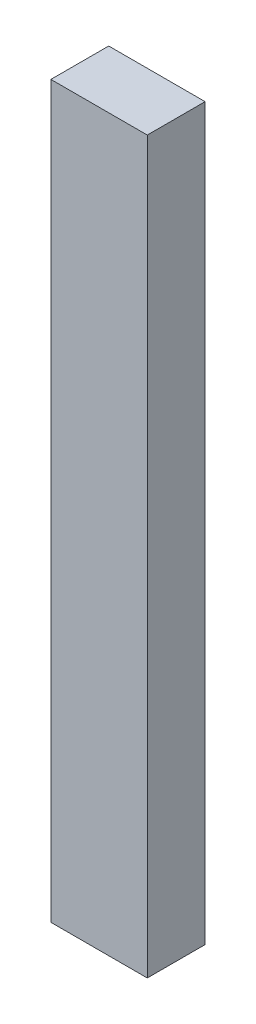
SolidWorks part; units mm, degrees
ref_plane "Front" through (0, 0, 0) normal (0, 0, 1) x (1, 0, 0)
ref_plane "Top" through (0, 0, 0) normal (0, 1, 0) x (1, 0, 0)
ref_plane "Right" through (0, 0, 0) normal (1, 0, 0) x (0, 0, -1)
sketch "Sketch1" plane through (0, 0, 0) normal (0, 0, 1) x (1, 0, 0)
  line L3 (63.5, 480.95) -> (63.5, 0) construction
  line L4 (0, 0) -> (480.95, 0)
  line L5 (480.95, 0) -> (480.95, 480.95)
  line L6 (480.95, 480.95) -> (0, 480.95)
  line L7 (0, 480.95) -> (0, 0)
  line L8 (0, 0) -> (63.5, 0)
  line L11 (0, 480.95) -> (0, 0)
  line L15 (63.5, 480.95) -> (63.5, 0)
  line L16 (63.5, 480.95) -> (0, 480.95)
  dimension "D1" = 0
extrude "Boss-Extrude1" add sketch "Sketch1" along normal blind 38.1
